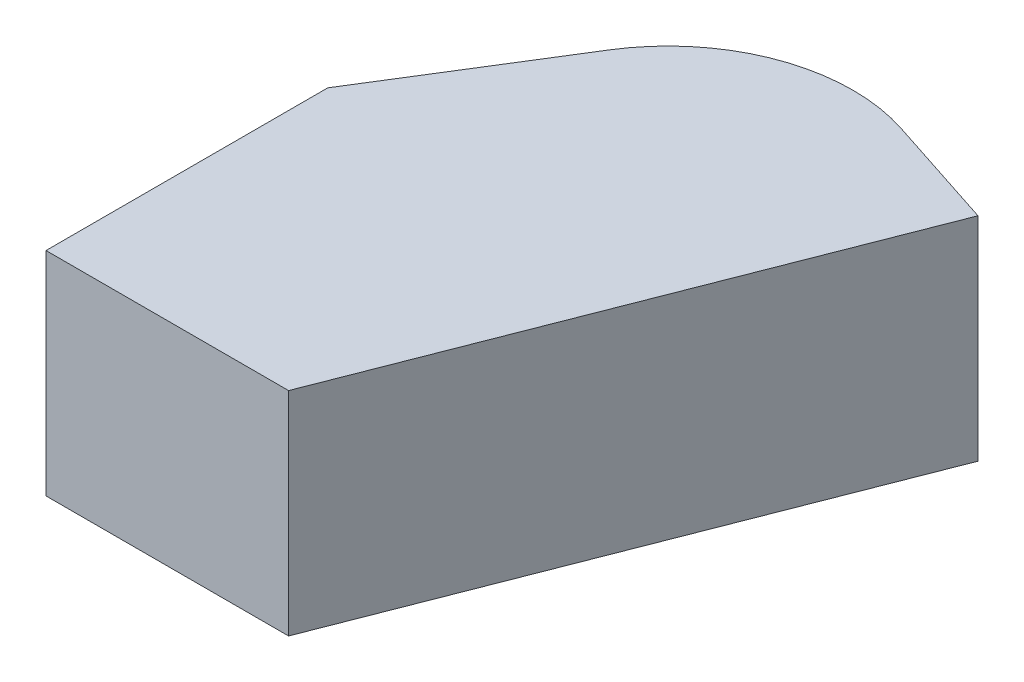
SolidWorks part; units mm, degrees
material "Pure Gold"
ref_plane "Front Plane" through (0, 0, 0) normal (0, 0, 1) x (1, 0, 0)
ref_plane "Top Plane" through (0, 0, 0) normal (0, 1, 0) x (1, 0, 0)
ref_plane "Right Plane" through (0, 0, 0) normal (1, 0, 0) x (0, 0, -1)
sketch "Sketch1" plane through (0, 0, 0) normal (0, 1, 0) x (1, 0, 0)
  line L0 (-66.6738, 0) -> (-37.0678, 47.6333)
  line L1 (0, 0) -> (-66.6738, 0) construction
  line L2 (0, 0) -> (0, -77.4519) construction
  line L3 (0, -77.4519) -> (-66.6738, -77.4519)
  line L4 (-66.6738, 0) -> (-66.6738, -77.4519)
  line L5 (21.8265, 69.1139) -> (53.1385, 58.9035)
  line L6 (53.1385, 58.9035) -> (0, -77.4519)
  arc A0 (-37.0678, 47.6333) -> (21.8265, 69.1139) centre (6.0775, 20.8169) cw
  dimension "D1" = 50.8
extrude "Boss-Extrude1" add sketch "Sketch1" along normal blind 58.42
